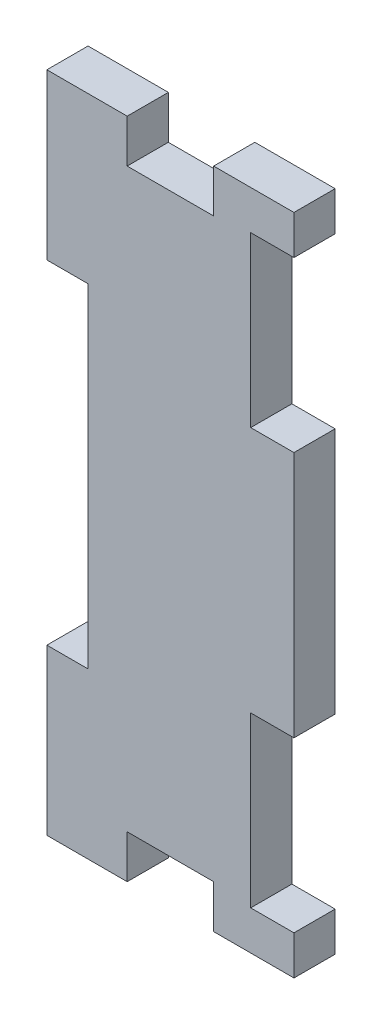
SolidWorks part; units mm, degrees
ref_plane "Front Plane" through (0, 0, 0) normal (0, 0, 1) x (1, 0, 0)
ref_plane "Top Plane" through (0, 0, 0) normal (0, 1, 0) x (1, 0, 0)
ref_plane "Right Plane" through (0, 0, 0) normal (1, 0, 0) x (0, 0, -1)
sketch "Model" plane through (0, 0, 0) normal (0, 0, 1) x (1, 0, 0)
  line L0 (83.7462, -134.0074) -> (83.7462, -154.0074)
  line L1 (108.4962, -98.7574) -> (108.4962, -78.2574)
  line L2 (83.7462, -154.0074) -> (93.4962, -154.0074)
  line L3 (88.7462, -134.0074) -> (83.7462, -134.0074)
  line L4 (113.7462, -149.2574) -> (113.7462, -154.0074)
  line L5 (88.7462, -134.0074) -> (88.7462, -93.5074)
  line L6 (113.7462, -128.7574) -> (108.4962, -128.7574)
  line L7 (113.7462, -98.7574) -> (108.4962, -98.7574)
  line L8 (93.4962, -73.5074) -> (93.4962, -78.7574)
  line L9 (113.7462, -128.7574) -> (113.7462, -98.7574)
  line L10 (93.4962, -78.7574) -> (103.9962, -78.7574)
  line L11 (113.7462, -78.2574) -> (113.7462, -73.5074)
  line L12 (103.9962, -78.7574) -> (103.9962, -73.5074)
  line L13 (103.9962, -148.7574) -> (103.9962, -154.0074)
  line L14 (103.9962, -73.5074) -> (113.7462, -73.5074)
  line L15 (83.7462, -73.5074) -> (93.4962, -73.5074)
  line L16 (93.4962, -148.7574) -> (103.9962, -148.7574)
  line L17 (83.7462, -93.5074) -> (83.7462, -73.5074)
  line L18 (108.4962, -149.2574) -> (113.7462, -149.2574)
  line L19 (93.4962, -154.0074) -> (93.4962, -148.7574)
  line L20 (103.9962, -154.0074) -> (113.7462, -154.0074)
  line L21 (88.7462, -93.5074) -> (83.7462, -93.5074)
  line L22 (108.4962, -128.7574) -> (108.4962, -149.2574)
  line L23 (108.4962, -78.2574) -> (113.7462, -78.2574)
  line L24 (93.9001, -105.5967) -> (93.9001, -121.9181)
  line L25 (108.6045, -111.5627) -> (108.7622, -111.8062)
  line L26 (112.6315, -109.958) -> (112.4786, -109.7192)
  line L27 (112.7751, -113.7543) -> (112.74, -114.1953)
  line L28 (112.2944, -109.6396) -> (108.948, -109.6396)
  line L29 (112.4786, -109.7192) -> (112.3904, -109.6595)
  line L30 (112.388, -111.8671) -> (112.4754, -111.8062)
  line L31 (112.7751, -110.7635) -> (112.7392, -111.1974)
  line L32 (108.7622, -111.8062) -> (108.8516, -111.8671)
  line L33 (108.948, -111.8874) -> (109.2539, -111.8874)
  line L34 (108.948, -114.8782) -> (108.8518, -114.8582)
  line L35 (112.7392, -111.1974) -> (112.6315, -111.5627)
  line L36 (108.948, -109.6396) -> (108.8492, -109.6595)
  line L37 (108.6045, -109.958) -> (108.5015, -110.3186)
  line L38 (112.4793, -112.7108) -> (112.6346, -112.952)
  line L39 (112.388, -111.8671) -> (112.2944, -111.8874)
  line L40 (112.74, -113.3134) -> (112.7751, -113.7543)
  line L41 (112.74, -114.1953) -> (112.6346, -114.5567)
  line L42 (111.9884, -114.8782) -> (112.2944, -114.8782)
  line L43 (112.7751, -110.7635) -> (112.7392, -110.3248)
  line L44 (112.74, -113.3134) -> (112.6346, -112.952)
  line L45 (112.4793, -112.7108) -> (112.3906, -112.6505)
  line L46 (112.3906, -112.6505) -> (112.2944, -112.6304)
  line L47 (112.2944, -112.6304) -> (108.948, -112.6304)
  line L48 (112.2944, -114.8782) -> (112.3906, -114.8582)
  line L49 (112.2944, -111.8874) -> (111.9884, -111.8874)
  line L50 (108.4672, -110.7635) -> (108.5015, -111.2068)
  line L51 (112.3904, -109.6595) -> (112.2944, -109.6396)
  line L52 (108.5015, -111.2068) -> (108.6045, -111.5627)
  line L53 (108.8516, -111.8671) -> (108.948, -111.8874)
  line L54 (112.4754, -111.8062) -> (112.6315, -111.5627)
  line L55 (112.4793, -114.7979) -> (112.3906, -114.8582)
  line L56 (108.5015, -110.3186) -> (108.4672, -110.7635)
  line L57 (112.7392, -110.3248) -> (112.6315, -109.958)
  line L58 (108.8492, -109.6595) -> (108.7591, -109.7192)
  line L59 (108.7591, -109.7192) -> (108.6045, -109.958)
  line L60 (112.4793, -114.7979) -> (112.6346, -114.5567)
  line L61 (108.763, -114.7979) -> (108.8518, -114.8582)
  line L62 (108.5023, -117.1923) -> (108.4672, -116.7513)
  line L63 (108.6077, -117.5536) -> (108.5023, -117.1923)
  line L64 (108.5023, -114.1953) -> (108.6077, -114.5567)
  line L65 (108.4672, -116.7513) -> (108.5023, -116.3103)
  line L66 (108.763, -115.7078) -> (108.6077, -115.9489)
  line L67 (108.763, -112.7108) -> (108.6077, -112.952)
  line L68 (108.8518, -112.6505) -> (108.763, -112.7108)
  line L69 (110.9131, -115.8459) -> (111.0395, -116.0769)
  line L70 (111.1394, -116.7513) -> (111.1043, -117.1923)
  line L71 (108.8518, -115.6475) -> (108.763, -115.7078)
  line L72 (110.9989, -117.5536) -> (110.8436, -117.7948)
  line L73 (108.6077, -114.5567) -> (108.763, -114.7979)
  line L74 (110.8436, -117.7948) -> (110.7548, -117.8551)
  line L75 (108.948, -115.6274) -> (108.8518, -115.6475)
  line L76 (108.948, -117.8752) -> (108.8518, -117.8551)
  line L77 (108.6077, -112.952) -> (108.5023, -113.3134)
  line L78 (110.6212, -114.8782) -> (108.948, -114.8782)
  line L79 (108.6077, -117.5536) -> (108.763, -117.7948)
  line L80 (112.7751, -117.8003) -> (112.7751, -115.6274)
  line L81 (111.0395, -116.0769) -> (111.1394, -116.7513)
  line L82 (108.8518, -117.8551) -> (108.763, -117.7948)
  line L83 (108.5023, -113.3134) -> (108.4672, -113.7543)
  line L84 (108.948, -117.8752) -> (110.6586, -117.8752)
  line L85 (110.6212, -113.7668) -> (110.6212, -114.8782)
  line L86 (112.7751, -115.6274) -> (110.6586, -115.6274)
  line L87 (110.9989, -117.5536) -> (111.1043, -117.1923)
  line L88 (110.7548, -117.8551) -> (110.6586, -117.8752)
  line L89 (108.4672, -113.7543) -> (108.5023, -114.1953)
  line L90 (108.5023, -116.3103) -> (108.6077, -115.9489)
  line L91 (110.6586, -115.6274) -> (110.9131, -115.8459)
  line L92 (108.948, -112.6304) -> (108.8518, -112.6505)
  line L93 (110.6212, -120.3752) -> (110.6212, -125.3752)
  line L94 (109.6212, -123.3752) -> (110.6212, -125.3752)
  line L95 (111.6212, -123.3752) -> (110.6212, -125.3752)
  line L96 (110.6212, -107.1396) -> (110.6212, -102.1396)
  line L97 (111.6212, -104.1396) -> (110.6212, -102.1396)
  line L98 (109.6212, -104.1396) -> (110.6212, -102.1396)
  line L99 (98.7462, -85.7574) -> (98.7462, -80.7574)
  line L100 (99.7462, -82.7574) -> (98.7462, -80.7574)
  line L101 (97.7462, -82.7574) -> (98.7462, -80.7574)
  line L102 (97.3789, -90.5052) -> (97.073, -90.5052)
  line L103 (97.073, -90.5052) -> (96.9766, -90.4849)
  line L104 (96.9766, -90.4849) -> (96.8872, -90.424)
  line L105 (96.8872, -90.424) -> (96.7295, -90.1805)
  line L106 (96.7295, -90.1805) -> (96.6265, -89.8246)
  line L107 (96.6265, -89.8246) -> (96.5922, -89.3813)
  line L108 (96.5922, -89.3813) -> (96.6265, -88.9364)
  line L109 (96.6265, -88.9364) -> (96.7295, -88.5759)
  line L110 (96.7295, -88.5759) -> (96.8841, -88.337)
  line L111 (96.8841, -88.337) -> (96.9742, -88.2773)
  line L112 (96.9742, -88.2773) -> (97.073, -88.2574)
  line L113 (97.073, -88.2574) -> (100.4194, -88.2574)
  line L114 (100.4194, -88.2574) -> (100.5154, -88.2773)
  line L115 (100.5154, -88.2773) -> (100.6036, -88.337)
  line L116 (100.6036, -88.337) -> (100.7565, -88.5759)
  line L117 (100.7565, -88.5759) -> (100.8642, -88.9427)
  line L118 (100.8642, -88.9427) -> (100.9001, -89.3813)
  line L119 (100.9001, -89.3813) -> (100.8642, -89.8153)
  line L120 (100.8642, -89.8153) -> (100.7565, -90.1805)
  line L121 (100.7565, -90.1805) -> (100.6004, -90.424)
  line L122 (100.6004, -90.424) -> (100.513, -90.4849)
  line L123 (100.513, -90.4849) -> (100.4194, -90.5052)
  line L124 (100.4194, -90.5052) -> (100.1134, -90.5052)
  line L125 (100.1134, -90.5052) -> (100.4194, -90.5052)
  line L126 (100.4194, -90.5052) -> (100.513, -90.4849)
  line L127 (100.513, -90.4849) -> (100.6004, -90.424)
  line L128 (100.6004, -90.424) -> (100.7565, -90.1805)
  line L129 (100.7565, -90.1805) -> (100.8642, -89.8153)
  line L130 (100.8642, -89.8153) -> (100.9001, -89.3813)
  line L131 (100.9001, -89.3813) -> (100.8642, -88.9427)
  line L132 (100.8642, -88.9427) -> (100.7565, -88.5759)
  line L133 (100.7565, -88.5759) -> (100.6036, -88.337)
  line L134 (100.6036, -88.337) -> (100.5154, -88.2773)
  line L135 (100.5154, -88.2773) -> (100.4194, -88.2574)
  line L136 (100.4194, -88.2574) -> (97.073, -88.2574)
  line L137 (97.073, -88.2574) -> (96.9742, -88.2773)
  line L138 (96.9742, -88.2773) -> (96.8841, -88.337)
  line L139 (96.8841, -88.337) -> (96.7295, -88.5759)
  line L140 (96.7295, -88.5759) -> (96.6265, -88.9364)
  line L141 (96.6265, -88.9364) -> (96.5922, -89.3813)
  line L142 (96.5922, -89.3813) -> (96.6265, -89.8246)
  line L143 (96.6265, -89.8246) -> (96.7295, -90.1805)
  line L144 (96.7295, -90.1805) -> (96.8872, -90.424)
  line L145 (96.8872, -90.424) -> (96.9766, -90.4849)
  line L146 (96.9766, -90.4849) -> (97.073, -90.5052)
  line L147 (97.073, -90.5052) -> (97.3789, -90.5052)
  line L148 (96.5922, -91.2483) -> (100.9001, -91.2483)
  line L149 (100.9001, -91.2483) -> (100.9001, -92.266)
  line L150 (100.9001, -92.266) -> (100.8642, -92.7)
  line L151 (100.8642, -92.7) -> (100.7565, -93.0652)
  line L152 (100.7565, -93.0652) -> (100.6004, -93.3088)
  line L153 (100.6004, -93.3088) -> (100.513, -93.3696)
  line L154 (100.513, -93.3696) -> (100.4194, -93.3899)
  line L155 (100.4194, -93.3899) -> (97.073, -93.3899)
  line L156 (97.073, -93.3899) -> (96.9766, -93.3696)
  line L157 (96.9766, -93.3696) -> (96.8872, -93.3088)
  line L158 (96.8872, -93.3088) -> (96.7295, -93.0652)
  line L159 (96.7295, -93.0652) -> (96.6265, -92.7093)
  line L160 (96.6265, -92.7093) -> (96.5922, -92.266)
  line L161 (96.5922, -92.266) -> (96.5922, -91.2483)
  line L162 (100.9001, -91.2483) -> (96.5922, -91.2483)
  line L163 (96.5922, -91.2483) -> (96.5922, -92.266)
  line L164 (96.5922, -92.266) -> (96.6265, -92.7093)
  line L165 (96.6265, -92.7093) -> (96.7295, -93.0652)
  line L166 (96.7295, -93.0652) -> (96.8872, -93.3088)
  line L167 (96.8872, -93.3088) -> (96.9766, -93.3696)
  line L168 (96.9766, -93.3696) -> (97.073, -93.3899)
  line L169 (97.073, -93.3899) -> (100.4194, -93.3899)
  line L170 (100.4194, -93.3899) -> (100.513, -93.3696)
  line L171 (100.513, -93.3696) -> (100.6004, -93.3088)
  line L172 (100.6004, -93.3088) -> (100.7565, -93.0652)
  line L173 (100.7565, -93.0652) -> (100.8642, -92.7)
  line L174 (100.8642, -92.7) -> (100.9001, -92.266)
  line L175 (100.9001, -92.266) -> (100.9001, -91.2483)
  line L176 (96.5922, -95.3691) -> (96.6273, -94.9281)
  line L177 (96.6273, -94.9281) -> (96.7327, -94.5668)
  line L178 (96.7327, -94.5668) -> (96.888, -94.3256)
  line L179 (96.888, -94.3256) -> (96.9768, -94.2653)
  line L180 (96.9768, -94.2653) -> (97.073, -94.2452)
  line L181 (97.073, -94.2452) -> (96.9768, -94.2653)
  line L182 (96.9768, -94.2653) -> (96.888, -94.3256)
  line L183 (96.888, -94.3256) -> (96.7327, -94.5668)
  line L184 (96.7327, -96.1715) -> (96.888, -96.4126)
  line L185 (96.888, -96.4126) -> (96.9768, -96.4729)
  line L186 (96.9768, -96.4729) -> (97.073, -96.493)
  line L187 (97.073, -96.493) -> (98.7836, -96.493)
  line L188 (98.7836, -96.493) -> (98.8798, -96.4729)
  line L189 (98.8798, -96.4729) -> (98.9686, -96.4126)
  line L190 (98.9686, -96.4126) -> (99.1239, -96.1715)
  line L191 (99.1239, -96.1715) -> (99.2293, -95.8101)
  line L192 (99.2293, -95.8101) -> (99.2644, -95.3691)
  line L193 (99.2644, -95.3691) -> (99.1645, -94.6948)
  line L194 (99.1645, -94.6948) -> (99.0381, -94.4637)
  line L195 (99.0381, -94.4637) -> (98.7836, -94.2452)
  line L196 (98.7836, -94.2452) -> (100.9001, -94.2452)
  line L197 (100.9001, -94.2452) -> (100.9001, -96.4181)
  line L198 (100.9001, -96.4181) -> (100.9001, -94.2452)
  line L199 (100.9001, -94.2452) -> (98.7836, -94.2452)
  line L200 (98.7836, -94.2452) -> (99.0381, -94.4637)
  line L201 (99.0381, -94.4637) -> (99.1645, -94.6948)
  line L202 (99.1645, -94.6948) -> (99.2644, -95.3691)
  line L203 (99.2644, -95.3691) -> (99.2293, -95.8101)
  line L204 (99.2293, -95.8101) -> (99.1239, -96.1715)
  line L205 (99.1239, -96.1715) -> (98.9686, -96.4126)
  line L206 (98.9686, -96.4126) -> (98.8798, -96.4729)
  line L207 (98.8798, -96.4729) -> (98.7836, -96.493)
  line L208 (98.7836, -96.493) -> (97.073, -96.493)
  line L209 (97.073, -96.493) -> (96.9768, -96.4729)
  line L210 (96.9768, -96.4729) -> (96.888, -96.4126)
  line L211 (96.888, -96.4126) -> (96.7327, -96.1715)
  line L212 (96.7327, -96.1715) -> (96.6273, -95.8101)
  line L213 (96.6273, -95.8101) -> (96.5922, -95.3691)
  line L214 (90.7462, -77.5074) -> (85.7462, -77.5074)
  line L215 (87.7462, -76.5074) -> (85.7462, -77.5074)
  line L216 (87.7462, -78.5074) -> (85.7462, -77.5074)
  line L217 (86.9129, -83.2552) -> (87.2188, -83.2552)
  line L218 (86.8165, -83.2349) -> (86.9129, -83.2552)
  line L219 (86.4321, -88.1191) -> (86.4673, -87.6781)
  line L220 (90.3553, -81.0273) -> (90.2593, -81.0074)
  line L221 (86.8167, -87.0153) -> (86.7279, -87.0756)
  line L222 (90.7462, -85.0597) -> (88.2548, -84.4478)
  line L223 (86.7271, -83.174) -> (86.8165, -83.2349)
  line L224 (86.5695, -82.9305) -> (86.7271, -83.174)
  line L225 (90.7042, -81.6927) -> (90.5965, -81.3259)
  line L226 (90.7401, -86.9952) -> (88.6235, -86.9952)
  line L227 (88.6235, -86.9952) -> (88.878, -87.2137)
  line L228 (86.8167, -87.0153) -> (86.9129, -86.9952)
  line L229 (88.2548, -84.4478) -> (88.2491, -85.7091)
  line L230 (86.4665, -81.6864) -> (86.4321, -82.1313)
  line L231 (90.7401, -86.9952) -> (90.7401, -89.1681)
  line L232 (88.878, -87.2137) -> (89.0044, -87.4448)
  line L233 (89.0044, -87.4448) -> (89.1043, -88.1191)
  line L234 (90.2593, -83.2552) -> (90.353, -83.2349)
  line L235 (90.2593, -81.0074) -> (86.9129, -81.0074)
  line L236 (86.724, -81.087) -> (86.5695, -81.3259)
  line L237 (86.4321, -82.1313) -> (86.4665, -82.5746)
  line L238 (86.4321, -86.1836) -> (88.2491, -85.7091)
  line L239 (88.2491, -85.7091) -> (90.7462, -85.0597)
  line L240 (86.4673, -87.6781) -> (86.5726, -87.3168)
  line L241 (86.5695, -81.3259) -> (86.4665, -81.6864)
  line L242 (90.4435, -81.087) -> (90.3553, -81.0273)
  line L243 (90.5965, -82.9305) -> (90.7042, -82.5653)
  line L244 (90.7042, -82.5653) -> (90.7401, -82.1313)
  line L245 (90.5965, -81.3259) -> (90.4435, -81.087)
  line L246 (86.8142, -81.0273) -> (86.724, -81.087)
  line L247 (86.7279, -87.0756) -> (86.5726, -87.3168)
  line L248 (90.2593, -83.2552) -> (89.9534, -83.2552)
  line L249 (90.7401, -82.1313) -> (90.7042, -81.6927)
  line L250 (86.9129, -81.0074) -> (86.8142, -81.0273)
  line L251 (90.353, -83.2349) -> (90.4404, -83.174)
  line L252 (86.4665, -82.5746) -> (86.5695, -82.9305)
  line L253 (90.4404, -83.174) -> (90.5965, -82.9305)
  line L254 (86.8167, -89.2229) -> (86.7279, -89.1626)
  line L255 (86.7279, -89.1626) -> (86.5726, -88.9215)
  line L256 (88.9639, -88.9215) -> (88.8085, -89.1626)
  line L257 (86.5726, -88.9215) -> (86.4673, -88.5601)
  line L258 (89.0692, -88.5601) -> (88.9639, -88.9215)
  line L259 (89.1043, -88.1191) -> (89.0692, -88.5601)
  line L260 (88.2548, -84.4478) -> (86.4321, -83.9983)
  line L261 (88.8085, -89.1626) -> (88.7198, -89.2229)
  line L262 (86.9129, -89.243) -> (86.8167, -89.2229)
  line L263 (86.4673, -88.5601) -> (86.4321, -88.1191)
  line L264 (88.7198, -89.2229) -> (88.6235, -89.243)
  line L265 (88.6235, -89.243) -> (86.9129, -89.243)
  line L266 (98.7462, -141.7574) -> (98.7462, -146.7574)
  line L267 (97.7462, -144.7574) -> (98.7462, -146.7574)
  line L268 (99.7462, -144.7574) -> (98.7462, -146.7574)
  line L269 (97.3789, -133.2696) -> (97.073, -133.2696)
  line L270 (97.073, -133.2696) -> (96.9766, -133.2493)
  line L271 (96.9766, -133.2493) -> (96.8872, -133.1884)
  line L272 (96.8872, -133.1884) -> (96.7295, -132.9449)
  line L273 (96.7295, -132.9449) -> (96.6265, -132.589)
  line L274 (96.6265, -132.589) -> (96.5922, -132.1457)
  line L275 (96.5922, -132.1457) -> (96.6265, -131.7008)
  line L276 (96.6265, -131.7008) -> (96.7295, -131.3402)
  line L277 (96.7295, -131.3402) -> (96.8841, -131.1014)
  line L278 (96.8841, -131.1014) -> (96.9742, -131.0417)
  line L279 (96.9742, -131.0417) -> (97.073, -131.0218)
  line L280 (97.073, -131.0218) -> (100.4194, -131.0218)
  line L281 (100.4194, -131.0218) -> (100.5154, -131.0417)
  line L282 (100.5154, -131.0417) -> (100.6036, -131.1014)
  line L283 (100.6036, -131.1014) -> (100.7565, -131.3402)
  line L284 (100.7565, -131.3402) -> (100.8642, -131.707)
  line L285 (100.8642, -131.707) -> (100.9001, -132.1457)
  line L286 (100.9001, -132.1457) -> (100.8642, -132.5796)
  line L287 (100.8642, -132.5796) -> (100.7565, -132.9449)
  line L288 (100.7565, -132.9449) -> (100.6004, -133.1884)
  line L289 (100.6004, -133.1884) -> (100.513, -133.2493)
  line L290 (100.513, -133.2493) -> (100.4194, -133.2696)
  line L291 (100.4194, -133.2696) -> (100.1134, -133.2696)
  line L292 (100.1134, -133.2696) -> (100.4194, -133.2696)
  line L293 (100.4194, -133.2696) -> (100.513, -133.2493)
  line L294 (100.513, -133.2493) -> (100.6004, -133.1884)
  line L295 (100.6004, -133.1884) -> (100.7565, -132.9449)
  line L296 (100.7565, -132.9449) -> (100.8642, -132.5796)
  line L297 (100.8642, -132.5796) -> (100.9001, -132.1457)
  line L298 (100.9001, -132.1457) -> (100.8642, -131.707)
  line L299 (100.8642, -131.707) -> (100.7565, -131.3402)
  line L300 (100.7565, -131.3402) -> (100.6036, -131.1014)
  line L301 (100.6036, -131.1014) -> (100.5154, -131.0417)
  line L302 (100.5154, -131.0417) -> (100.4194, -131.0218)
  line L303 (100.4194, -131.0218) -> (97.073, -131.0218)
  line L304 (97.073, -131.0218) -> (96.9742, -131.0417)
  line L305 (96.9742, -131.0417) -> (96.8841, -131.1014)
  line L306 (96.8841, -131.1014) -> (96.7295, -131.3402)
  line L307 (96.7295, -131.3402) -> (96.6265, -131.7008)
  line L308 (96.6265, -131.7008) -> (96.5922, -132.1457)
  line L309 (96.5922, -132.1457) -> (96.6265, -132.589)
  line L310 (96.6265, -132.589) -> (96.7295, -132.9449)
  line L311 (96.7295, -132.9449) -> (96.8872, -133.1884)
  line L312 (96.8872, -133.1884) -> (96.9766, -133.2493)
  line L313 (96.9766, -133.2493) -> (97.073, -133.2696)
  line L314 (97.073, -133.2696) -> (97.3789, -133.2696)
  line L315 (96.5922, -134.0126) -> (100.9001, -134.0126)
  line L316 (100.9001, -134.0126) -> (100.9001, -135.0304)
  line L317 (100.9001, -135.0304) -> (100.8642, -135.4643)
  line L318 (100.8642, -135.4643) -> (100.7565, -135.8296)
  line L319 (100.7565, -135.8296) -> (100.6004, -136.0731)
  line L320 (100.6004, -136.0731) -> (100.513, -136.134)
  line L321 (100.513, -136.134) -> (100.4194, -136.1543)
  line L322 (100.4194, -136.1543) -> (97.073, -136.1543)
  line L323 (97.073, -136.1543) -> (96.9766, -136.134)
  line L324 (96.9766, -136.134) -> (96.8872, -136.0731)
  line L325 (96.8872, -136.0731) -> (96.7295, -135.8296)
  line L326 (96.7295, -135.8296) -> (96.6265, -135.4737)
  line L327 (96.6265, -135.4737) -> (96.5922, -135.0304)
  line L328 (96.5922, -135.0304) -> (96.5922, -134.0126)
  line L329 (100.9001, -134.0126) -> (96.5922, -134.0126)
  line L330 (96.5922, -134.0126) -> (96.5922, -135.0304)
  line L331 (96.5922, -135.0304) -> (96.6265, -135.4737)
  line L332 (96.6265, -135.4737) -> (96.7295, -135.8296)
  line L333 (96.7295, -135.8296) -> (96.8872, -136.0731)
  line L334 (96.8872, -136.0731) -> (96.9766, -136.134)
  line L335 (96.9766, -136.134) -> (97.073, -136.1543)
  line L336 (97.073, -136.1543) -> (100.4194, -136.1543)
  line L337 (100.4194, -136.1543) -> (100.513, -136.134)
  line L338 (100.513, -136.134) -> (100.6004, -136.0731)
  line L339 (100.6004, -136.0731) -> (100.7565, -135.8296)
  line L340 (100.7565, -135.8296) -> (100.8642, -135.4643)
  line L341 (100.8642, -135.4643) -> (100.9001, -135.0304)
  line L342 (100.9001, -135.0304) -> (100.9001, -134.0126)
  line L343 (96.5922, -138.1335) -> (96.6273, -137.6925)
  line L344 (96.6273, -137.6925) -> (96.7327, -137.3311)
  line L345 (96.7327, -137.3311) -> (96.888, -137.09)
  line L346 (96.888, -137.09) -> (96.9768, -137.0297)
  line L347 (96.9768, -137.0297) -> (97.073, -137.0096)
  line L348 (97.073, -137.0096) -> (96.9768, -137.0297)
  line L349 (96.9768, -137.0297) -> (96.888, -137.09)
  line L350 (96.888, -137.09) -> (96.7327, -137.3311)
  line L351 (96.7327, -138.9358) -> (96.888, -139.177)
  line L352 (96.888, -139.177) -> (96.9768, -139.2373)
  line L353 (96.9768, -139.2373) -> (97.073, -139.2574)
  line L354 (97.073, -139.2574) -> (98.7836, -139.2574)
  line L355 (98.7836, -139.2574) -> (98.8798, -139.2373)
  line L356 (98.8798, -139.2373) -> (98.9686, -139.177)
  line L357 (98.9686, -139.177) -> (99.1239, -138.9358)
  line L358 (99.1239, -138.9358) -> (99.2293, -138.5745)
  line L359 (99.2293, -138.5745) -> (99.2644, -138.1335)
  line L360 (99.2644, -138.1335) -> (99.1645, -137.4591)
  line L361 (99.1645, -137.4591) -> (99.0381, -137.2281)
  line L362 (99.0381, -137.2281) -> (98.7836, -137.0096)
  line L363 (98.7836, -137.0096) -> (100.9001, -137.0096)
  line L364 (100.9001, -137.0096) -> (100.9001, -139.1824)
  line L365 (100.9001, -139.1824) -> (100.9001, -137.0096)
  line L366 (100.9001, -137.0096) -> (98.7836, -137.0096)
  line L367 (98.7836, -137.0096) -> (99.0381, -137.2281)
  line L368 (99.0381, -137.2281) -> (99.1645, -137.4591)
  line L369 (99.1645, -137.4591) -> (99.2644, -138.1335)
  line L370 (99.2644, -138.1335) -> (99.2293, -138.5745)
  line L371 (99.2293, -138.5745) -> (99.1239, -138.9358)
  line L372 (99.1239, -138.9358) -> (98.9686, -139.177)
  line L373 (98.9686, -139.177) -> (98.8798, -139.2373)
  line L374 (98.8798, -139.2373) -> (98.7836, -139.2574)
  line L375 (98.7836, -139.2574) -> (97.073, -139.2574)
  line L376 (97.073, -139.2574) -> (96.9768, -139.2373)
  line L377 (96.9768, -139.2373) -> (96.888, -139.177)
  line L378 (96.888, -139.177) -> (96.7327, -138.9358)
  line L379 (96.7327, -138.9358) -> (96.6273, -138.5745)
  line L380 (96.6273, -138.5745) -> (96.5922, -138.1335)
  line L381 (96.4735, -110.0923) -> (95.8616, -110.0923)
  line L382 (95.8616, -110.0923) -> (95.6689, -110.0517)
  line L383 (95.6689, -110.0517) -> (95.4901, -109.93)
  line L384 (95.4901, -109.93) -> (95.1748, -109.4429)
  line L385 (95.1748, -109.4429) -> (94.9688, -108.7312)
  line L386 (94.9688, -108.7312) -> (94.9001, -107.8445)
  line L387 (94.9001, -107.8445) -> (94.9688, -106.9548)
  line L388 (94.9688, -106.9548) -> (95.1748, -106.2336)
  line L389 (95.1748, -106.2336) -> (95.4839, -105.7559)
  line L390 (95.4839, -105.7559) -> (95.6642, -105.6365)
  line L391 (95.6642, -105.6365) -> (95.8616, -105.5967)
  line L392 (95.8616, -105.5967) -> (102.5545, -105.5967)
  line L393 (102.5545, -105.5967) -> (102.7465, -105.6365)
  line L394 (102.7465, -105.6365) -> (102.9229, -105.7559)
  line L395 (102.9229, -105.7559) -> (103.2288, -106.2336)
  line L396 (103.2288, -106.2336) -> (103.4442, -106.9672)
  line L397 (103.4442, -106.9672) -> (103.516, -107.8445)
  line L398 (103.516, -107.8445) -> (103.4442, -108.7124)
  line L399 (103.4442, -108.7124) -> (103.2288, -109.4429)
  line L400 (103.2288, -109.4429) -> (102.9166, -109.93)
  line L401 (102.9166, -109.93) -> (102.7418, -110.0517)
  line L402 (102.7418, -110.0517) -> (102.5545, -110.0923)
  line L403 (102.5545, -110.0923) -> (101.9426, -110.0923)
  line L404 (101.9426, -110.0923) -> (102.5545, -110.0923)
  line L405 (102.5545, -110.0923) -> (102.7418, -110.0517)
  line L406 (102.7418, -110.0517) -> (102.9166, -109.93)
  line L407 (102.9166, -109.93) -> (103.2288, -109.4429)
  line L408 (103.2288, -109.4429) -> (103.4442, -108.7124)
  line L409 (103.4442, -108.7124) -> (103.516, -107.8445)
  line L410 (103.516, -107.8445) -> (103.4442, -106.9672)
  line L411 (103.4442, -106.9672) -> (103.2288, -106.2336)
  line L412 (103.2288, -106.2336) -> (102.9229, -105.7559)
  line L413 (102.9229, -105.7559) -> (102.7465, -105.6365)
  line L414 (102.7465, -105.6365) -> (102.5545, -105.5967)
  line L415 (102.5545, -105.5967) -> (95.8616, -105.5967)
  line L416 (95.8616, -105.5967) -> (95.6642, -105.6365)
  line L417 (95.6642, -105.6365) -> (95.4839, -105.7559)
  line L418 (95.4839, -105.7559) -> (95.1748, -106.2336)
  line L419 (95.1748, -106.2336) -> (94.9688, -106.9548)
  line L420 (94.9688, -106.9548) -> (94.9001, -107.8445)
  line L421 (94.9001, -107.8445) -> (94.9688, -108.7312)
  line L422 (94.9688, -108.7312) -> (95.1748, -109.4429)
  line L423 (95.1748, -109.4429) -> (95.4901, -109.93)
  line L424 (95.4901, -109.93) -> (95.6689, -110.0517)
  line L425 (95.6689, -110.0517) -> (95.8616, -110.0923)
  line L426 (95.8616, -110.0923) -> (96.4735, -110.0923)
  line L427 (94.9001, -111.5784) -> (103.516, -111.5784)
  line L428 (103.516, -111.5784) -> (103.516, -115.8368)
  line L429 (103.516, -115.8368) -> (103.516, -111.5784)
  line L430 (103.516, -111.5784) -> (99.333, -111.5784)
  line L431 (99.333, -111.5784) -> (99.333, -115.2373)
  line L432 (99.333, -115.2373) -> (99.333, -111.5784)
  line L433 (99.333, -111.5784) -> (94.9001, -111.5784)
  line L434 (94.9001, -111.5784) -> (94.9001, -115.8368)
  line L435 (94.9001, -115.8368) -> (94.9001, -111.5784)
  line L436 (94.9001, -119.8201) -> (94.9704, -118.9382)
  line L437 (94.9704, -118.9382) -> (95.1811, -118.2154)
  line L438 (95.1811, -118.2154) -> (95.4917, -117.7331)
  line L439 (95.4917, -117.7331) -> (95.6693, -117.6125)
  line L440 (95.6693, -117.6125) -> (95.8616, -117.5723)
  line L441 (95.8616, -117.5723) -> (95.6693, -117.6125)
  line L442 (95.6693, -117.6125) -> (95.4917, -117.7331)
  line L443 (95.4917, -117.7331) -> (95.1811, -118.2154)
  line L444 (95.1811, -121.4248) -> (95.4917, -121.9072)
  line L445 (95.4917, -121.9072) -> (95.6693, -122.0277)
  line L446 (95.6693, -122.0277) -> (95.8616, -122.0679)
  line L447 (95.8616, -122.0679) -> (99.2829, -122.0679)
  line L448 (99.2829, -122.0679) -> (99.4754, -122.0277)
  line L449 (99.4754, -122.0277) -> (99.6529, -121.9072)
  line L450 (99.6529, -121.9072) -> (99.9636, -121.4248)
  line L451 (99.9636, -121.4248) -> (100.1743, -120.7021)
  line L452 (100.1743, -120.7021) -> (100.2445, -119.8201)
  line L453 (100.2445, -119.8201) -> (100.0447, -118.4714)
  line L454 (100.0447, -118.4714) -> (99.7918, -118.0094)
  line L455 (99.7918, -118.0094) -> (99.2829, -117.5723)
  line L456 (99.2829, -117.5723) -> (103.516, -117.5723)
  line L457 (103.516, -117.5723) -> (103.516, -121.9181)
  line L458 (103.516, -121.9181) -> (103.516, -117.5723)
  line L459 (103.516, -117.5723) -> (99.2829, -117.5723)
  line L460 (99.2829, -117.5723) -> (99.7918, -118.0094)
  line L461 (99.7918, -118.0094) -> (100.0447, -118.4714)
  line L462 (100.0447, -118.4714) -> (100.2445, -119.8201)
  line L463 (100.2445, -119.8201) -> (100.1743, -120.7021)
  line L464 (100.1743, -120.7021) -> (99.9636, -121.4248)
  line L465 (99.9636, -121.4248) -> (99.6529, -121.9072)
  line L466 (99.6529, -121.9072) -> (99.4754, -122.0277)
  line L467 (99.4754, -122.0277) -> (99.2829, -122.0679)
  line L468 (99.2829, -122.0679) -> (95.8616, -122.0679)
  line L469 (95.8616, -122.0679) -> (95.6693, -122.0277)
  line L470 (95.6693, -122.0277) -> (95.4917, -121.9072)
  line L471 (95.4917, -121.9072) -> (95.1811, -121.4248)
  line L472 (95.1811, -121.4248) -> (94.9704, -120.7021)
  line L473 (94.9704, -120.7021) -> (94.9001, -119.8201)
  line L474 (92.9001, -107.0935) -> (92.9001, -106.5534)
  line L475 (92.9001, -106.5534) -> (92.9001, -107.6242)
  line L476 (92.9001, -107.6242) -> (92.9001, -107.0935)
  line L477 (92.9001, -107.0935) -> (90.7462, -107.0935)
  line L478 (90.7462, -107.0935) -> (92.9001, -107.0935)
  line L479 (90.7462, -108.0519) -> (92.9001, -108.0519)
  line L480 (92.9001, -108.0519) -> (91.8387, -108.0519)
  line L481 (91.8387, -108.0519) -> (91.8387, -109.1695)
  line L482 (91.8387, -109.1695) -> (92.9001, -109.1695)
  line L483 (92.9001, -109.1695) -> (90.7462, -109.1695)
  line L484 (90.7462, -109.1695) -> (91.8388, -109.1695)
  line L485 (91.8388, -109.1695) -> (91.8388, -108.0519)
  line L486 (91.8388, -108.0519) -> (90.7462, -108.0519)
  line L487 (92.9032, -109.5504) -> (90.7462, -109.5504)
  line L488 (91.1395, -110.0504) -> (90.9865, -110.0504)
  line L489 (90.9865, -110.0504) -> (90.9384, -110.0604)
  line L490 (90.9384, -110.0604) -> (90.8941, -110.0906)
  line L491 (90.8941, -110.0906) -> (90.8164, -110.2111)
  line L492 (90.8164, -110.2111) -> (90.7637, -110.3918)
  line L493 (90.7637, -110.3918) -> (90.7462, -110.6123)
  line L494 (90.7462, -110.6123) -> (90.7637, -110.8328)
  line L495 (90.7637, -110.8328) -> (90.8164, -111.0135)
  line L496 (90.8164, -111.0135) -> (90.8941, -111.1341)
  line L497 (90.8941, -111.1341) -> (90.9384, -111.1642)
  line L498 (90.9384, -111.1642) -> (90.9865, -111.1743)
  line L499 (90.9865, -111.1743) -> (91.6234, -111.1805)
  line L500 (91.6234, -111.1805) -> (91.7492, -111.1523)
  line L501 (91.7492, -111.1523) -> (91.8395, -111.0708)
  line L502 (91.8395, -111.0708) -> (91.8944, -110.9361)
  line L503 (91.8944, -110.9361) -> (91.9137, -110.7481)
  line L504 (91.9137, -110.7481) -> (91.9223, -110.4074)
  line L505 (91.9223, -110.4074) -> (91.9418, -110.2439)
  line L506 (91.9418, -110.2439) -> (92.0237, -110.0987)
  line L507 (92.0237, -110.0987) -> (92.0723, -110.0625)
  line L508 (92.0723, -110.0625) -> (92.126, -110.0504)
  line L509 (92.126, -110.0504) -> (92.6598, -110.0504)
  line L510 (92.6598, -110.0504) -> (92.7078, -110.0604)
  line L511 (92.7078, -110.0604) -> (92.7522, -110.0906)
  line L512 (92.7522, -110.0906) -> (92.8299, -110.2111)
  line L513 (92.8299, -110.2111) -> (92.8826, -110.3918)
  line L514 (92.8826, -110.3918) -> (92.9001, -110.6123)
  line L515 (92.9001, -110.6123) -> (92.8826, -110.8328)
  line L516 (92.8826, -110.8328) -> (92.8299, -111.0135)
  line L517 (92.8299, -111.0135) -> (92.7522, -111.1341)
  line L518 (92.7522, -111.1341) -> (92.7078, -111.1642)
  line L519 (92.7078, -111.1642) -> (92.6598, -111.1743)
  line L520 (92.6598, -111.1743) -> (92.5068, -111.1743)
  line L521 (92.5068, -111.1743) -> (92.6598, -111.1743)
  line L522 (92.6598, -111.1743) -> (92.7078, -111.1642)
  line L523 (92.7078, -111.1642) -> (92.7522, -111.1341)
  line L524 (92.7522, -111.1341) -> (92.8299, -111.0135)
  line L525 (92.8299, -111.0135) -> (92.8826, -110.8328)
  line L526 (92.8826, -110.8328) -> (92.9001, -110.6123)
  line L527 (92.9001, -110.6123) -> (92.8826, -110.3918)
  line L528 (92.8826, -110.3918) -> (92.8299, -110.2111)
  line L529 (92.8299, -110.2111) -> (92.7522, -110.0906)
  line L530 (92.7522, -110.0906) -> (92.7078, -110.0604)
  line L531 (92.7078, -110.0604) -> (92.6598, -110.0504)
  line L532 (92.6598, -110.0504) -> (92.126, -110.0504)
  line L533 (92.126, -110.0504) -> (92.0723, -110.0625)
  line L534 (92.0723, -110.0625) -> (92.0237, -110.0987)
  line L535 (92.0237, -110.0987) -> (91.9418, -110.2439)
  line L536 (91.9418, -110.2439) -> (91.9223, -110.4074)
  line L537 (91.9223, -110.4074) -> (91.9137, -110.7481)
  line L538 (91.9137, -110.7481) -> (91.8944, -110.9361)
  line L539 (91.8944, -110.9361) -> (91.8395, -111.0708)
  line L540 (91.8395, -111.0708) -> (91.7492, -111.1523)
  line L541 (91.7492, -111.1523) -> (91.6234, -111.1805)
  line L542 (91.6234, -111.1805) -> (90.9865, -111.1743)
  line L543 (90.9865, -111.1743) -> (90.9384, -111.1642)
  line L544 (90.9384, -111.1642) -> (90.8941, -111.1341)
  line L545 (90.8941, -111.1341) -> (90.8164, -111.0135)
  line L546 (90.8164, -111.0135) -> (90.7637, -110.8328)
  line L547 (90.7637, -110.8328) -> (90.7462, -110.6123)
  line L548 (90.7462, -110.6123) -> (90.7637, -110.3918)
  line L549 (90.7637, -110.3918) -> (90.8164, -110.2111)
  line L550 (90.8164, -110.2111) -> (90.8941, -110.0906)
  line L551 (90.8941, -110.0906) -> (90.9384, -110.0604)
  line L552 (90.9384, -110.0604) -> (90.9865, -110.0504)
  line L553 (90.9865, -110.0504) -> (91.1395, -110.0504)
  line L554 (91.1395, -112.7943) -> (90.9865, -112.7943)
  line L555 (90.9865, -112.7943) -> (90.9384, -112.8043)
  line L556 (90.9384, -112.8043) -> (90.8941, -112.8345)
  line L557 (90.8941, -112.8345) -> (90.8164, -112.955)
  line L558 (90.8164, -112.955) -> (90.7637, -113.1357)
  line L559 (90.7637, -113.1357) -> (90.7462, -113.3562)
  line L560 (90.7462, -113.3562) -> (90.7637, -113.5767)
  line L561 (90.7637, -113.5767) -> (90.8164, -113.7574)
  line L562 (90.8164, -113.7574) -> (90.8941, -113.878)
  line L563 (90.8941, -113.878) -> (90.9384, -113.9081)
  line L564 (90.9384, -113.9081) -> (90.9865, -113.9182)
  line L565 (90.9865, -113.9182) -> (91.6234, -113.9244)
  line L566 (91.6234, -113.9244) -> (91.7492, -113.8962)
  line L567 (91.7492, -113.8962) -> (91.8395, -113.8148)
  line L568 (91.8395, -113.8148) -> (91.8944, -113.68)
  line L569 (91.8944, -113.68) -> (91.9137, -113.492)
  line L570 (91.9137, -113.492) -> (91.9223, -113.1513)
  line L571 (91.9223, -113.1513) -> (91.9418, -112.9878)
  line L572 (91.9418, -112.9878) -> (92.0237, -112.8427)
  line L573 (92.0237, -112.8427) -> (92.0723, -112.8064)
  line L574 (92.0723, -112.8064) -> (92.126, -112.7943)
  line L575 (92.126, -112.7943) -> (92.6598, -112.7943)
  line L576 (92.6598, -112.7943) -> (92.7078, -112.8043)
  line L577 (92.7078, -112.8043) -> (92.7522, -112.8345)
  line L578 (92.7522, -112.8345) -> (92.8299, -112.955)
  line L579 (92.8299, -112.955) -> (92.8826, -113.1357)
  line L580 (92.8826, -113.1357) -> (92.9001, -113.3562)
  line L581 (92.9001, -113.3562) -> (92.8826, -113.5767)
  line L582 (92.8826, -113.5767) -> (92.8299, -113.7574)
  line L583 (92.8299, -113.7574) -> (92.7522, -113.878)
  line L584 (92.7522, -113.878) -> (92.7078, -113.9081)
  line L585 (92.7078, -113.9081) -> (92.6598, -113.9182)
  line L586 (92.6598, -113.9182) -> (92.5068, -113.9182)
  line L587 (92.5068, -113.9182) -> (92.6598, -113.9182)
  line L588 (92.6598, -113.9182) -> (92.7078, -113.9081)
  line L589 (92.7078, -113.9081) -> (92.7522, -113.878)
  line L590 (92.7522, -113.878) -> (92.8299, -113.7574)
  line L591 (92.8299, -113.7574) -> (92.8826, -113.5767)
  line L592 (92.8826, -113.5767) -> (92.9001, -113.3562)
  line L593 (92.9001, -113.3562) -> (92.8826, -113.1357)
  line L594 (92.8826, -113.1357) -> (92.8299, -112.955)
  line L595 (92.8299, -112.955) -> (92.7522, -112.8345)
  line L596 (92.7522, -112.8345) -> (92.7078, -112.8043)
  line L597 (92.7078, -112.8043) -> (92.6598, -112.7943)
  line L598 (92.6598, -112.7943) -> (92.126, -112.7943)
  line L599 (92.126, -112.7943) -> (92.0723, -112.8064)
  line L600 (92.0723, -112.8064) -> (92.0237, -112.8427)
  line L601 (92.0237, -112.8427) -> (91.9418, -112.9878)
  line L602 (91.9418, -112.9878) -> (91.9223, -113.1513)
  line L603 (91.9223, -113.1513) -> (91.9137, -113.492)
  line L604 (91.9137, -113.492) -> (91.8944, -113.68)
  line L605 (91.8944, -113.68) -> (91.8395, -113.8148)
  line L606 (91.8395, -113.8148) -> (91.7492, -113.8962)
  line L607 (91.7492, -113.8962) -> (91.6234, -113.9244)
  line L608 (91.6234, -113.9244) -> (90.9865, -113.9182)
  line L609 (90.9865, -113.9182) -> (90.9384, -113.9081)
  line L610 (90.9384, -113.9081) -> (90.8941, -113.878)
  line L611 (90.8941, -113.878) -> (90.8164, -113.7574)
  line L612 (90.8164, -113.7574) -> (90.7637, -113.5767)
  line L613 (90.7637, -113.5767) -> (90.7462, -113.3562)
  line L614 (90.7462, -113.3562) -> (90.7637, -113.1357)
  line L615 (90.7637, -113.1357) -> (90.8164, -112.955)
  line L616 (90.8164, -112.955) -> (90.8941, -112.8345)
  line L617 (90.8941, -112.8345) -> (90.9384, -112.8043)
  line L618 (90.9384, -112.8043) -> (90.9865, -112.7943)
  line L619 (90.9865, -112.7943) -> (91.1395, -112.7943)
  line L620 (92.9032, -114.2897) -> (90.7462, -114.2897)
  line L621 (90.7462, -114.7897) -> (92.9001, -114.7897)
  line L622 (92.9001, -114.7897) -> (92.9001, -115.2986)
  line L623 (92.9001, -115.2986) -> (92.8822, -115.5155)
  line L624 (92.8822, -115.5155) -> (92.8283, -115.6982)
  line L625 (92.8283, -115.6982) -> (92.7503, -115.8199)
  line L626 (92.7503, -115.8199) -> (92.7066, -115.8504)
  line L627 (92.7066, -115.8504) -> (92.6598, -115.8605)
  line L628 (92.6598, -115.8605) -> (90.9865, -115.8605)
  line L629 (90.9865, -115.8605) -> (90.9383, -115.8504)
  line L630 (90.9383, -115.8504) -> (90.8937, -115.8199)
  line L631 (90.8937, -115.8199) -> (90.8148, -115.6982)
  line L632 (90.8148, -115.6982) -> (90.7633, -115.5202)
  line L633 (90.7633, -115.5202) -> (90.7462, -115.2986)
  line L634 (90.7462, -115.2986) -> (90.7462, -114.7897)
  line L635 (92.9001, -114.7897) -> (90.7462, -114.7897)
  line L636 (90.7462, -114.7897) -> (90.7462, -115.2986)
  line L637 (90.7462, -115.2986) -> (90.7633, -115.5202)
  line L638 (90.7633, -115.5202) -> (90.8148, -115.6982)
  line L639 (90.8148, -115.6982) -> (90.8937, -115.8199)
  line L640 (90.8937, -115.8199) -> (90.9383, -115.8504)
  line L641 (90.9383, -115.8504) -> (90.9865, -115.8605)
  line L642 (90.9865, -115.8605) -> (92.6598, -115.8605)
  line L643 (92.6598, -115.8605) -> (92.7066, -115.8504)
  line L644 (92.7066, -115.8504) -> (92.7503, -115.8199)
  line L645 (92.7503, -115.8199) -> (92.8283, -115.6982)
  line L646 (92.8283, -115.6982) -> (92.8822, -115.5155)
  line L647 (92.8822, -115.5155) -> (92.9001, -115.2986)
  line L648 (92.9001, -115.2986) -> (92.9001, -114.7897)
  line L649 (90.7462, -116.2882) -> (92.9001, -116.2882)
  line L650 (92.9001, -116.2882) -> (92.9001, -117.3528)
  line L651 (92.9001, -117.3528) -> (92.9001, -116.2882)
  line L652 (92.9001, -116.2882) -> (91.8544, -116.2882)
  line L653 (91.8544, -116.2882) -> (91.8544, -117.2029)
  line L654 (91.8544, -117.2029) -> (91.8544, -116.2882)
  line L655 (91.8544, -116.2882) -> (90.7462, -116.2882)
  line L656 (90.7462, -116.2882) -> (90.7462, -117.3528)
  line L657 (90.7462, -117.3528) -> (90.7462, -116.2882)
  line L658 (92.9032, -119.0351) -> (90.7462, -119.0351)
  line L659 (90.7462, -119.5351) -> (92.9001, -119.5351)
  line L660 (92.9001, -119.5351) -> (90.7462, -120.6153)
  line L661 (90.7462, -120.6153) -> (92.9001, -120.6153)
  line L662 (92.9001, -120.6153) -> (90.7462, -120.6153)
  line L663 (90.7462, -120.6153) -> (92.9001, -119.5351)
  line L664 (92.9001, -119.5351) -> (90.7462, -119.5351)
  line L665 (90.7462, -138.0074) -> (85.7462, -138.0074)
  line L666 (87.7462, -137.0074) -> (85.7462, -138.0074)
  line L667 (87.7462, -139.0074) -> (85.7462, -138.0074)
  line L668 (86.9129, -143.7552) -> (87.2188, -143.7552)
  line L669 (86.8165, -143.7349) -> (86.9129, -143.7552)
  line L670 (86.4321, -148.6191) -> (86.4673, -148.1781)
  line L671 (90.3553, -141.5273) -> (90.2593, -141.5074)
  line L672 (86.8167, -147.5153) -> (86.7279, -147.5756)
  line L673 (90.7462, -145.5597) -> (88.2548, -144.9478)
  line L674 (86.7271, -143.674) -> (86.8165, -143.7349)
  line L675 (86.5695, -143.4305) -> (86.7271, -143.674)
  line L676 (90.7042, -142.1926) -> (90.5965, -141.8258)
  line L677 (90.7401, -147.4952) -> (88.6235, -147.4952)
  line L678 (88.6235, -147.4952) -> (88.878, -147.7137)
  line L679 (86.8167, -147.5153) -> (86.9129, -147.4952)
  line L680 (88.2548, -144.9478) -> (88.2491, -146.2091)
  line L681 (86.4665, -142.1864) -> (86.4321, -142.6313)
  line L682 (90.7401, -147.4952) -> (90.7401, -149.6681)
  line L683 (88.878, -147.7137) -> (89.0044, -147.9447)
  line L684 (89.0044, -147.9447) -> (89.1043, -148.6191)
  line L685 (90.2593, -143.7552) -> (90.353, -143.7349)
  line L686 (90.2593, -141.5074) -> (86.9129, -141.5074)
  line L687 (86.724, -141.587) -> (86.5695, -141.8258)
  line L688 (86.4321, -142.6313) -> (86.4665, -143.0746)
  line L689 (86.4321, -146.6836) -> (88.2491, -146.2091)
  line L690 (88.2491, -146.2091) -> (90.7462, -145.5597)
  line L691 (86.4673, -148.1781) -> (86.5726, -147.8167)
  line L692 (86.5695, -141.8258) -> (86.4665, -142.1864)
  line L693 (90.4435, -141.587) -> (90.3553, -141.5273)
  line L694 (90.5965, -143.4305) -> (90.7042, -143.0652)
  line L695 (90.7042, -143.0652) -> (90.7401, -142.6313)
  line L696 (90.5965, -141.8258) -> (90.4435, -141.587)
  line L697 (86.8142, -141.5273) -> (86.724, -141.587)
  line L698 (86.7279, -147.5756) -> (86.5726, -147.8167)
  line L699 (90.2593, -143.7552) -> (89.9534, -143.7552)
  line L700 (90.7401, -142.6313) -> (90.7042, -142.1926)
  line L701 (86.9129, -141.5074) -> (86.8142, -141.5273)
  line L702 (90.353, -143.7349) -> (90.4404, -143.674)
  line L703 (86.4665, -143.0746) -> (86.5695, -143.4305)
  line L704 (90.4404, -143.674) -> (90.5965, -143.4305)
  line L705 (86.8167, -149.7229) -> (86.7279, -149.6626)
  line L706 (86.7279, -149.6626) -> (86.5726, -149.4214)
  line L707 (88.9639, -149.4214) -> (88.8085, -149.6626)
  line L708 (86.5726, -149.4214) -> (86.4673, -149.0601)
  line L709 (89.0692, -149.0601) -> (88.9639, -149.4214)
  line L710 (89.1043, -148.6191) -> (89.0692, -149.0601)
  line L711 (88.2548, -144.9478) -> (86.4321, -144.4982)
  line L712 (88.8085, -149.6626) -> (88.7198, -149.7229)
  line L713 (86.9129, -149.743) -> (86.8167, -149.7229)
  line L714 (86.4673, -149.0601) -> (86.4321, -148.6191)
  line L715 (88.7198, -149.7229) -> (88.6235, -149.743)
  line L716 (88.6235, -149.743) -> (86.9129, -149.743)
sketch "Sketch2" plane through (0, 0, 0) normal (0, 0, 1) x (1, 0, 0)
  line L0 (113.7462, -98.7574) -> (108.4962, -98.7574) construction
  line L1 (113.7462, -128.7574) -> (113.7462, -98.7574) construction
  line L2 (113.7462, -128.7574) -> (108.4962, -128.7574) construction
  line L3 (108.4962, -128.7574) -> (108.4962, -149.2574) construction
  line L4 (108.4962, -149.2574) -> (113.7462, -149.2574) construction
  line L5 (113.7462, -149.2574) -> (113.7462, -154.0074) construction
  line L6 (103.9962, -154.0074) -> (113.7462, -154.0074) construction
  line L7 (103.9962, -148.7574) -> (103.9962, -154.0074) construction
  line L8 (93.4962, -148.7574) -> (103.9962, -148.7574) construction
  line L9 (93.4962, -154.0074) -> (93.4962, -148.7574) construction
  line L10 (83.7462, -154.0074) -> (93.4962, -154.0074) construction
  line L11 (83.7462, -134.0074) -> (83.7462, -154.0074) construction
  line L12 (88.7462, -134.0074) -> (83.7462, -134.0074) construction
  line L13 (88.7462, -134.0074) -> (88.7462, -93.5074) construction
  line L14 (88.7462, -93.5074) -> (83.7462, -93.5074) construction
  line L15 (83.7462, -93.5074) -> (83.7462, -73.5074) construction
  line L16 (83.7462, -73.5074) -> (93.4962, -73.5074) construction
  line L17 (93.4962, -73.5074) -> (93.4962, -78.7574) construction
  line L18 (93.4962, -78.7574) -> (103.9962, -78.7574) construction
  line L19 (103.9962, -78.7574) -> (103.9962, -73.5074) construction
  line L20 (103.9962, -73.5074) -> (113.7462, -73.5074) construction
  line L21 (113.7462, -78.2574) -> (113.7462, -73.5074) construction
  line L22 (108.4962, -78.2574) -> (113.7462, -78.2574) construction
  line L23 (108.4962, -98.7574) -> (108.4962, -78.2574) construction
  line L24 (113.7462, -98.7574) -> (108.4962, -98.7574)
  line L25 (113.7462, -128.7574) -> (113.7462, -98.7574)
  line L26 (113.7462, -128.7574) -> (108.4962, -128.7574)
  line L27 (108.4962, -128.7574) -> (108.4962, -149.2574)
  line L28 (108.4962, -149.2574) -> (113.7462, -149.2574)
  line L29 (113.7462, -149.2574) -> (113.7462, -154.0074)
  line L30 (103.9962, -154.0074) -> (113.7462, -154.0074)
  line L31 (103.9962, -148.7574) -> (103.9962, -154.0074)
  line L32 (93.4962, -148.7574) -> (103.9962, -148.7574)
  line L33 (93.4962, -154.0074) -> (93.4962, -148.7574)
  line L34 (83.7462, -154.0074) -> (93.4962, -154.0074)
  line L35 (83.7462, -134.0074) -> (83.7462, -154.0074)
  line L36 (88.7462, -134.0074) -> (83.7462, -134.0074)
  line L37 (88.7462, -134.0074) -> (88.7462, -93.5074)
  line L38 (88.7462, -93.5074) -> (83.7462, -93.5074)
  line L39 (83.7462, -93.5074) -> (83.7462, -73.5074)
  line L40 (83.7462, -73.5074) -> (93.4962, -73.5074)
  line L41 (93.4962, -73.5074) -> (93.4962, -78.7574)
  line L42 (93.4962, -78.7574) -> (103.9962, -78.7574)
  line L43 (103.9962, -78.7574) -> (103.9962, -73.5074)
  line L44 (103.9962, -73.5074) -> (113.7462, -73.5074)
  line L45 (113.7462, -78.2574) -> (113.7462, -73.5074)
  line L46 (108.4962, -78.2574) -> (113.7462, -78.2574)
  line L47 (108.4962, -98.7574) -> (108.4962, -78.2574)
  line L48 (113.7462, -113.7574) -> (98.7462, -113.7574) construction
  line L49 (98.7462, -78.7574) -> (98.7462, -113.7574) construction
  point P10 (98.043, -113.7574)
extrude "Boss-Extrude1" add sketch "Sketch2" along normal mid plane 5
ref_plane "Plane1" through (0, -113.7574, 0) normal (0, 1, 0) x (1, 0, 0)
ref_plane "Plane2" through (98.7462, 0, 0) normal (1, 0, 0) x (0, 0, -1)
